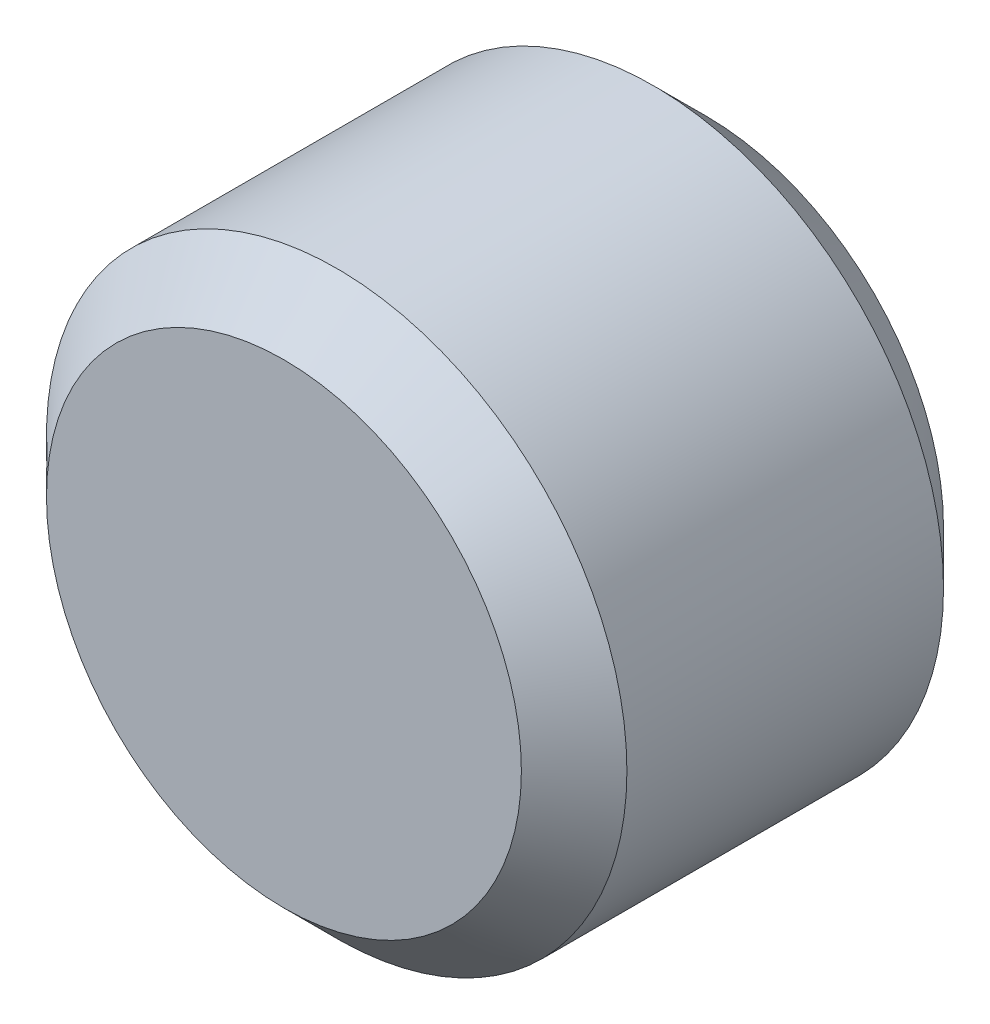
SolidWorks part; units mm, degrees
ref_plane "정면" through (0, 0, 0) normal (0, 0, 1) x (1, 0, 0)
ref_plane "윗면" through (0, 0, 0) normal (0, 1, 0) x (1, 0, 0)
ref_plane "우측면" through (0, 0, 0) normal (1, 0, 0) x (0, 0, -1)
sketch "스케치1" plane through (0, 0, 0) normal (0, 0, 1) x (1, 0, 0)
  circle A0 centre (0, 0) radius 2.75
  dimension "D1" = 5.5
extrude "보스-돌출1" add sketch "스케치1" along normal blind 1.5
sketch "스케치2" plane through (0, 0, 0) normal (0, 0, 1) x (1, 0, 0)
  circle A0 centre (0, 0) radius 1
  circle A1 centre (0, 0) radius 2.75
  dimension "D1" = 2
  dimension "D2" = 5.5
extrude "보스-돌출2" add sketch "스케치2" against normal blind 2.5
chamfer "모따기1" distance 0.5 angle 45 2 edges at (2.75, 0, 1.5) (2.75, 0, -2.5)
